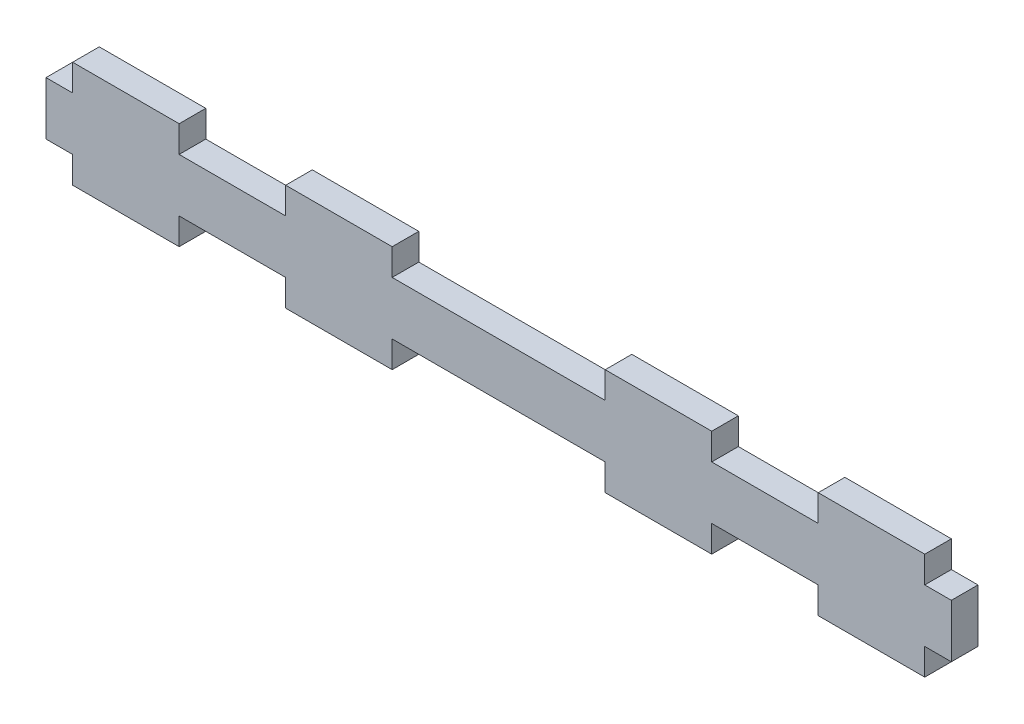
SolidWorks part; units mm, degrees
material "Beech"
ref_plane "Front" through (0, 0, 0) normal (0, 0, 1) x (1, 0, 0)
ref_plane "Top" through (0, 0, 0) normal (0, 1, 0) x (1, 0, 0)
ref_plane "Right" through (0, 0, 0) normal (1, 0, 0) x (0, 0, -1)
sketch "Sketch1" plane through (0, 0, 0) normal (0, 0, 1) x (1, 0, 0)
  line L0 (-42.5, 5) -> (42.5, 5) construction
  line L1 (-40, -2.5) -> (40, -2.5) construction
  line L2 (-40, -2.5) -> (-40, 2.5) construction
  line L3 (-40, 2.5) -> (40, 2.5) construction
  line L4 (40, -2.5) -> (40, 2.5) construction
  line L5 (-40, -2.5) -> (40, 2.5) construction
  line L6 (-40, 2.5) -> (40, -2.5) construction
  line L7 (42.5, -5) -> (42.5, 5) construction
  line L8 (-42.5, -5) -> (42.5, -5) construction
  line L9 (-42.5, -5) -> (-42.5, 5) construction
  line L10 (-42.5, 2.5) -> (-40, 2.5)
  line L11 (-40, 2.5) -> (-40, 5)
  line L12 (-40, 5) -> (-30, 5)
  line L13 (-30, 5) -> (-30, 2.5)
  line L14 (-30, 2.5) -> (-20, 2.5)
  line L15 (-20, 2.5) -> (-20, 5)
  line L16 (-20, 5) -> (-10, 5)
  line L17 (-10, 5) -> (-10, 2.5)
  line L18 (-10, 2.5) -> (10, 2.5)
  line L19 (0, -1.2441) -> (0, 1.3602) construction
  line L20 (-10, 0) -> (9.6842, 0) construction
  line L21 (10, 5) -> (10, 2.5)
  line L22 (20, 5) -> (10, 5)
  line L23 (20, 2.5) -> (20, 5)
  line L24 (30, 2.5) -> (20, 2.5)
  line L25 (30, 5) -> (30, 2.5)
  line L26 (40, 5) -> (30, 5)
  line L27 (40, 2.5) -> (40, 5)
  line L28 (42.5, 2.5) -> (40, 2.5)
  line L29 (42.5, -2.5) -> (40, -2.5)
  line L30 (40, -2.5) -> (40, -5)
  line L31 (40, -5) -> (30, -5)
  line L32 (30, -5) -> (30, -2.5)
  line L33 (30, -2.5) -> (20, -2.5)
  line L34 (20, -2.5) -> (20, -5)
  line L35 (20, -5) -> (10, -5)
  line L36 (10, -5) -> (10, -2.5)
  line L37 (-10, -2.5) -> (10, -2.5)
  line L38 (-10, -5) -> (-10, -2.5)
  line L39 (-20, -5) -> (-10, -5)
  line L40 (-20, -2.5) -> (-20, -5)
  line L41 (-30, -2.5) -> (-20, -2.5)
  line L42 (-30, -5) -> (-30, -2.5)
  line L43 (-40, -5) -> (-30, -5)
  line L44 (-40, -2.5) -> (-40, -5)
  line L45 (-42.5, -2.5) -> (-40, -2.5)
  line L46 (-42.5, 2.5) -> (-42.5, -2.5)
  line L47 (42.5, 2.5) -> (42.5, -2.5)
  point P0 (0, 0)
  point P24 (0, 2.5)
  dimension "D2" = 85
  dimension "D3" = 10
  dimension "D4" = 10
  dimension "D1" = 2.5
extrude "Boss-Extrude1" add sketch "Sketch1" along normal blind 2.5
